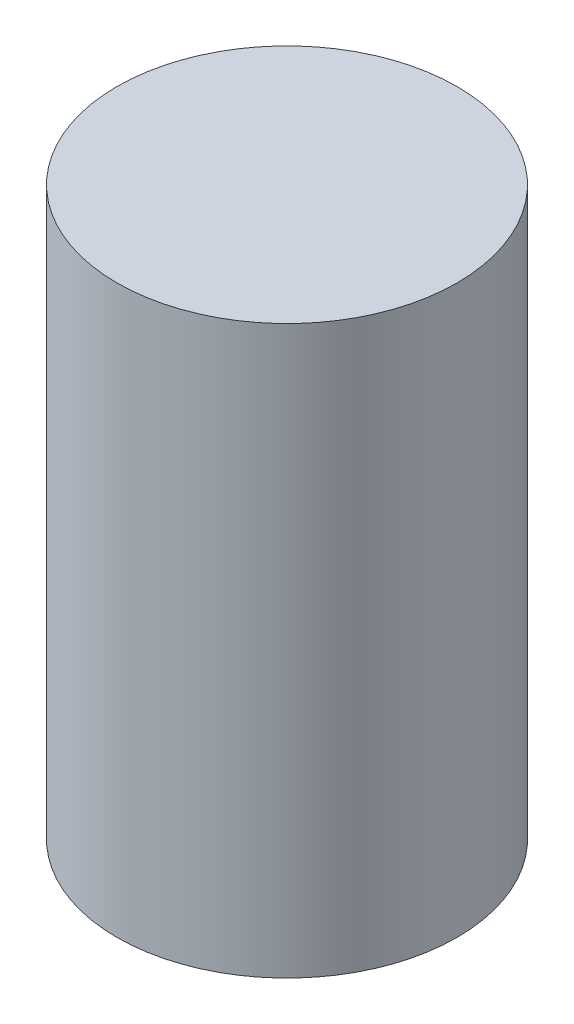
SolidWorks part; units mm, degrees
ref_plane "Front" through (0, 0, 0) normal (0, 0, 1) x (1, 0, 0)
ref_plane "Top" through (0, 0, 0) normal (0, 1, 0) x (1, 0, 0)
ref_plane "Right" through (0, 0, 0) normal (1, 0, 0) x (0, 0, -1)
sketch "Sketch1" plane through (0, 0, 0) normal (0, 1, 0) x (1, 0, 0)
  circle A0 centre (0, 0) radius 1.5
  dimension "D1" = 3
extrude "Boss-Extrude1" add sketch "Sketch1" against normal blind 5
